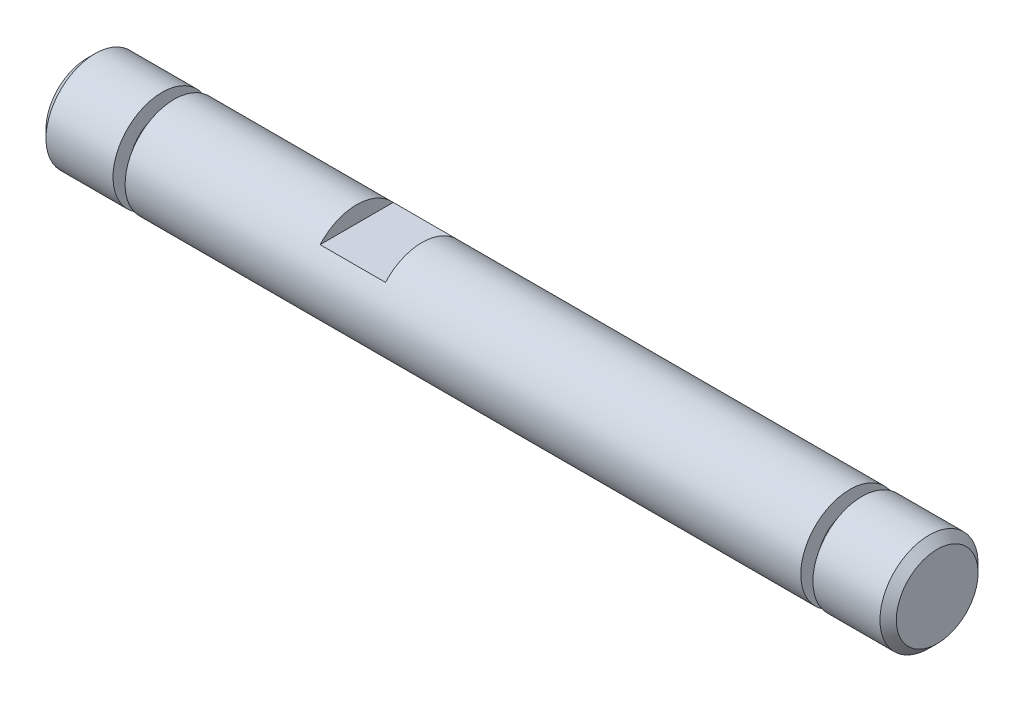
SolidWorks part; units mm, degrees
ref_plane "Plan de face" through (0, 0, 0) normal (0, 0, 1) x (1, 0, 0)
ref_plane "Plan de dessus" through (0, 0, 0) normal (0, 1, 0) x (1, 0, 0)
ref_plane "Plan de droite" through (0, 0, 0) normal (1, 0, 0) x (0, 0, -1)
sketch "Esquisse1" plane through (0, 0, 0) normal (0, 0, 1) x (1, 0, 0)
  line L0 (0, 0) -> (12.8037, 0) construction
  line L1 (0, 0) -> (0, 15.5366) construction
  line L2 (26, 0) -> (-26, 0)
  line L4 (-26, 0) -> (-26, 3)
  line L5 (-26, 3) -> (26, 3)
  line L6 (26, 0) -> (26, 3)
  point P10 (0, 0)
  dimension "D1" = 52
  dimension "D2" = 3
revolve "Révolution1" add sketch "Esquisse1" angle 360 about L0
chamfer "Chanfrein1" distance 0.5 angle 45 2 edges at (-26, 0, 3) (26, 0, 3)
sketch "Esquisse2" plane through (0, 0, 0) normal (0, 0, 1) x (1, 0, 0)
  line L0 (25.5, 3) -> (-25.5, 3) construction
  line L1 (25.5, 3) -> (-25.5, 3)
  line L3 (-9.5, 4) -> (-5.5, 4)
  line L4 (-9.5, 4) -> (-9.5, 2)
  line L5 (-9.5, 2) -> (-5.5, 2)
  line L6 (-5.5, 4) -> (-5.5, 2)
  line L7 (-9.5, 4) -> (-5.5, 2) construction
  line L8 (-9.5, 2) -> (-5.5, 4) construction
  point P2 (-7.5, 3)
  dimension "D1" = 1
  dimension "D2" = 7.5
  dimension "D3" = 4
extrude "Enlèv. mat.-Extru.1" cut sketch "Esquisse2" against normal through all both and the other way through all contours L5 L6 L3 L4
sketch "Esquisse3" plane through (0, 0, 0) normal (0, 0, 1) x (1, 0, 0)
  line L2 (-9.5, 3) -> (-25.5, 3) construction
  line L3 (-21.4, 3) -> (-20.66, 3)
  line L4 (0, 0) -> (0, 10.3249) construction
  line L5 (-21.4, 3) -> (-21.4, 2)
  line L6 (-21.4, 2) -> (-20.66, 2)
  line L7 (-20.66, 3) -> (-20.66, 2)
  line L8 (20.66, 3) -> (20.66, 2)
  line L9 (21.4, 2) -> (20.66, 2)
  line L10 (21.4, 3) -> (21.4, 2)
  line L11 (21.4, 3) -> (20.66, 3)
  line L17 (0, 0) -> (-35.8372, 0) construction
  dimension "D1" = 0.74
  dimension "D2" = 2
  dimension "D3" = 42.8
revolve "Enlèvement de matière-Révolution1" cut sketch "Esquisse3" angle 360 about L17
